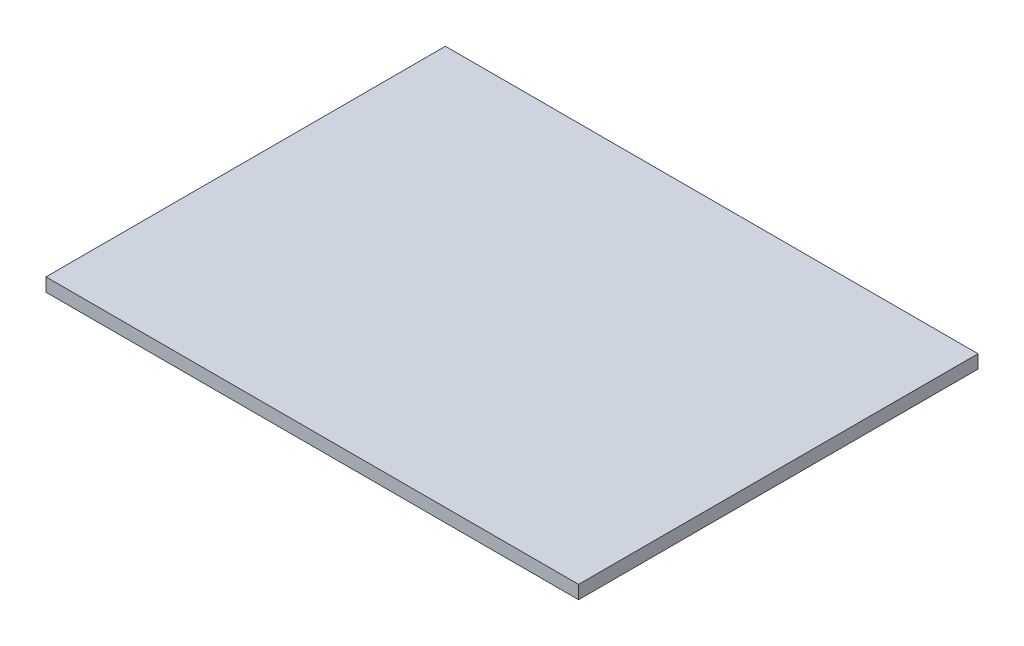
SolidWorks part; units mm, degrees
ref_plane "정면" through (0, 0, 0) normal (0, 0, 1) x (1, 0, 0)
ref_plane "윗면" through (0, 0, 0) normal (0, 1, 0) x (1, 0, 0)
ref_plane "우측면" through (0, 0, 0) normal (1, 0, 0) x (0, 0, -1)
sketch "스케치1" plane through (0, 0, 0) normal (0, 1, 0) x (1, 0, 0)
  line L1 (-100, -75) -> (100, -75)
  line L2 (-100, -75) -> (-100, 75)
  line L3 (-100, 75) -> (100, 75)
  line L4 (100, -75) -> (100, 75)
  line L5 (-100, -75) -> (100, 75) construction
  line L6 (-100, 75) -> (100, -75) construction
  point P0 (0, 0)
  dimension "D1" = 200
  dimension "D2" = 150
extrude "보스-돌출1" add sketch "스케치1" along normal blind 5
